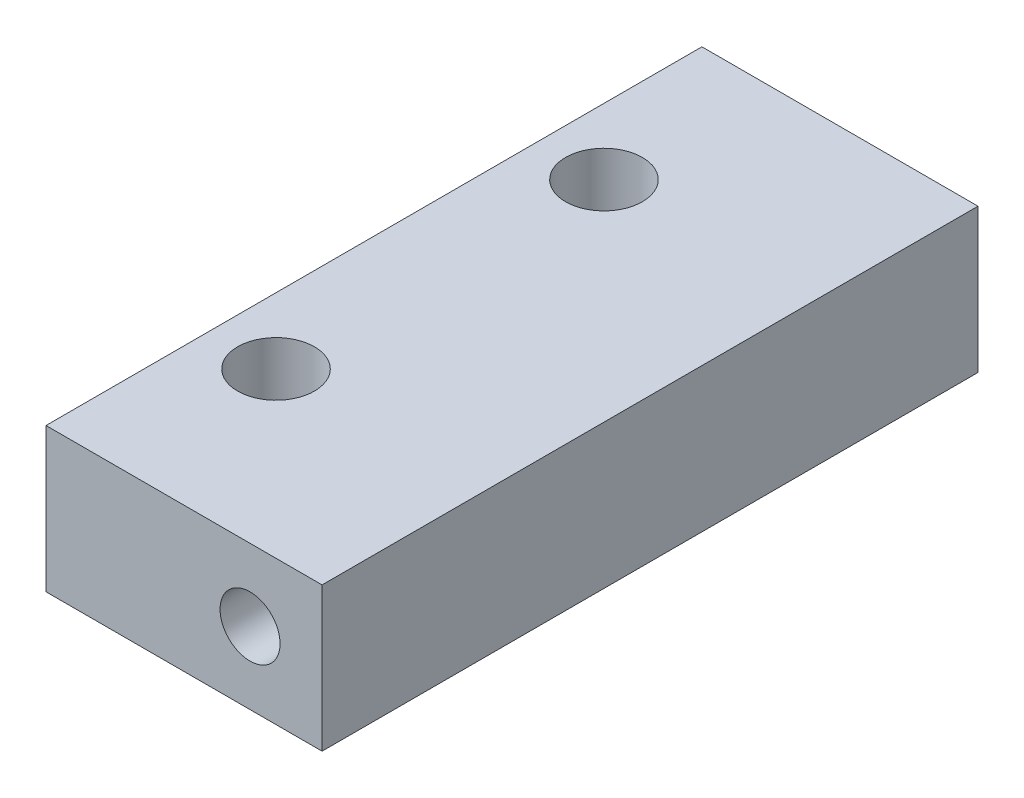
SolidWorks part; units mm, degrees
ref_plane "Front" through (0, 0, 0) normal (0, 0, 1) x (1, 0, 0)
ref_plane "Top" through (0, 0, 0) normal (0, 1, 0) x (1, 0, 0)
ref_plane "Right" through (0, 0, 0) normal (1, 0, 0) x (0, 0, -1)
sketch "Sketch1" plane through (0, 0, 0) normal (0, 1, 0) x (1, 0, 0)
  line L0 (0, 27.323) -> (5.5, 27.323)
  line L1 (0, 0) -> (11.5, 0)
  line L2 (0, 0) -> (0, 27.323)
  line L3 (0, 27.323) -> (11.5, 27.323)
  line L4 (11.5, 0) -> (11.5, 27.323)
  line L5 (2.75, 27.323) -> (2.75, 0)
  line L6 (2.75, 13.6615) -> (2.75, 20.492)
  line L7 (2.75, 13.6615) -> (2.75, 6.831)
  circle A0 centre (2.75, 20.492) radius 1.6
  circle A1 centre (2.75, 6.831) radius 1.6
  dimension "D1" = 27.323
  dimension "D2" = 11.5
  dimension "D3" = 5.5
  dimension "D4" = 6.8305
  dimension "D5" = 6.8305
extrude "Boss-Extrude1" add sketch "Sketch1" along normal blind 6 contours A1 L5 L1 L4 L3 A0 L6 | A1 L5 L6 A0 L0 L2 L1
sketch "Sketch2" plane through (0, 0, 0) normal (0, 0, 1) x (1, 0, 0)
  line L0 (11.5, 6) -> (5.5, 6)
  line L1 (0, 6) -> (11.5, 6) construction
  line L2 (8.5, 6) -> (8.5, 0)
  line L3 (0, 0) -> (11.5, 0) construction
  circle A0 centre (8.5, 3) radius 1.25
  dimension "D1" = 6
extrude "Cut-Extrude1" cut sketch "Sketch2" against normal through all contours A0
